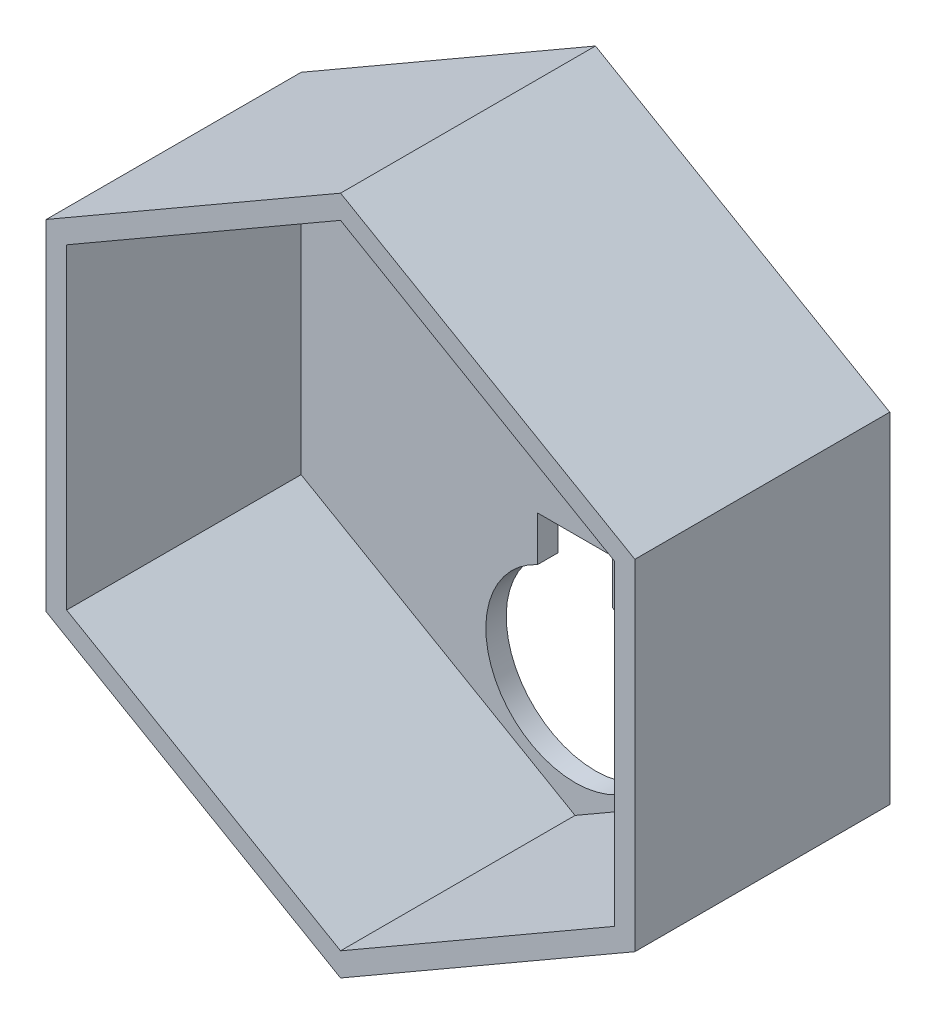
SolidWorks part; units mm, degrees
ref_plane "Спереди" through (0, 0, 0) normal (0, 0, 1) x (1, 0, 0)
ref_plane "Сверху" through (0, 0, 0) normal (0, 1, 0) x (1, 0, 0)
ref_plane "Справа" through (0, 0, 0) normal (1, 0, 0) x (0, 0, -1)
sketch "Skizze1" plane through (0, 0, 0) normal (0, 0, 1) x (1, 0, 0)
  line L0 (0, 0) -> (0, -26.3562) construction
  line L8 (0, -20) -> (17.3205, -10)
  line L9 (17.3205, -10) -> (17.3205, 10)
  line L10 (17.3205, 10) -> (0, 20)
  line L11 (0, 20) -> (-17.3205, 10)
  line L12 (-17.3205, 10) -> (-17.3205, -10)
  line L13 (-17.3205, -10) -> (0, -20)
  circle A1 centre (0, 0) radius 17.3205 construction
  dimension "D2" = 20
extrude "Linear-Austragen-Dünn1" add sketch "Skizze1" along normal blind 15 thin thin type one direction reverse wall 1.2
sketch "Skizze2" plane through (0, 0, 0) normal (0, 0, -1) x (-1, 0, 0)
  line L0 (-16.1205, -9.3072) -> (-16.1205, 9.3072) construction
  line L1 (0, -18.6144) -> (-16.1205, -9.3072) construction
  line L2 (16.1205, -9.3072) -> (0, -18.6144) construction
  line L3 (16.1205, 9.3072) -> (16.1205, -9.3072) construction
  line L4 (0, 18.6144) -> (16.1205, 9.3072) construction
  line L5 (-16.1205, 9.3072) -> (0, 18.6144) construction
  line L6 (-16.1205, -9.3072) -> (-16.1205, 9.3072)
  line L7 (0, -18.6144) -> (-16.1205, -9.3072)
  line L8 (16.1205, -9.3072) -> (0, -18.6144)
  line L9 (16.1205, 9.3072) -> (16.1205, -9.3072)
  line L10 (0, 18.6144) -> (16.1205, 9.3072)
  line L11 (-16.1205, 9.3072) -> (0, 18.6144)
extrude "Aufsatz-Linear austragen1" add sketch "Skizze2" against normal blind 1.2
sketch "Skizze3" plane through (0, 0, 1.2) normal (0, 0, 1) x (1, 0, 0)
  circle A0 centre (0, -11.6953) radius 5.25
  dimension "D1" = 10.5
extrude "Schnitt-Linear austragen1" cut sketch "Skizze3" against normal blind 1.2
sketch "Skizze4" plane through (0, 0, 1.2) normal (0, 0, 1) x (1, 0, 0)
  line L0 (0, 0) -> (0, -14.6296) construction
  line L1 (-2.2, -4.3) -> (2.2, -4.3)
  line L2 (-2.2, -4.3) -> (-2.2, -9.0076)
  line L3 (-2.2, -9.0076) -> (2.2, -9.0076)
  line L4 (2.2, -4.3) -> (2.2, -9.0076)
  dimension "D1" = 4.4
  dimension "D2" = 2.2
  dimension "D3" = 4.3
  dimension "D4" = 4.7076
extrude "Schnitt-Linear austragen2" cut sketch "Skizze4" against normal blind 1.2
